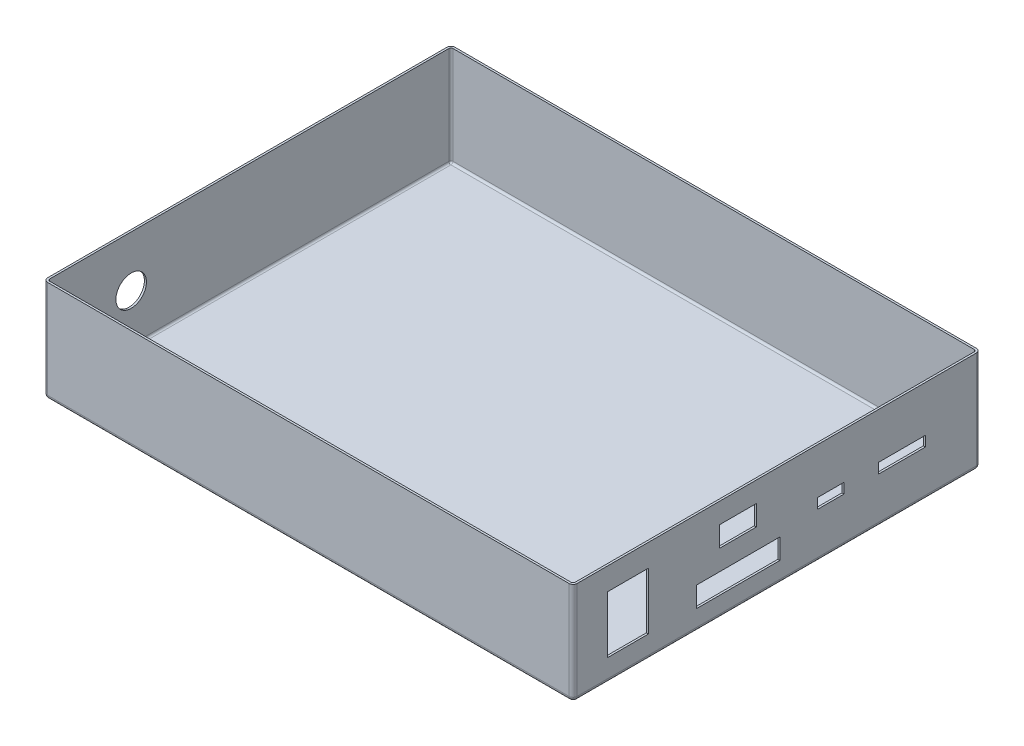
SolidWorks part; units mm, degrees
ref_plane "Front Plane" through (0, 0, 0) normal (0, 0, 1) x (1, 0, 0)
ref_plane "Top Plane" through (0, 0, 0) normal (0, 1, 0) x (1, 0, 0)
ref_plane "Right Plane" through (0, 0, 0) normal (1, 0, 0) x (0, 0, -1)
sketch "Sketch1" plane through (0, 0, 0) normal (0, 1, 0) x (1, 0, 0)
  line L1 (130, -100) -> (-130, -100)
  line L2 (130, -100) -> (130, 100)
  line L3 (130, 100) -> (-130, 100)
  line L4 (-130, -100) -> (-130, 100)
  line L5 (130, -100) -> (-130, 100) construction
  line L6 (130, 100) -> (-130, -100) construction
  point P0 (0, 0)
  dimension "D1" = 260
  dimension "D2" = 200
extrude "Boss-Extrude1" add sketch "Sketch1" along normal blind 50
fillet "Fillet1" radius 2 8 edges at (0, 0, 100) (-130, 25, 100) (-130, 0, 0) (-130, 25, -100) (0, 0, -100) (130, 0, 0) (130, 25, -100) (130, 25, 100)
shell "Shell1" thickness 1
sketch "Sketch2" plane through (130, 0, 0) normal (1, 0, 0) x (0, 0, -1)
  line L0 (-144.0315, 25) -> (119.5021, 25) construction
  line L1 (-98, 50) -> (98, 50) construction
  line L2 (-100, 0) -> (100, 0) construction
  line L3 (98, 2) -> (98, 50) construction
  line L4 (-39.5, 10) -> (1.5, 10)
  line L5 (-39.5, 10) -> (-39.5, 20)
  line L6 (-39.5, 20) -> (1.5, 20)
  line L7 (1.5, 10) -> (1.5, 20)
  line L8 (-39.5, 10) -> (1.5, 20) construction
  line L9 (-39.5, 20) -> (1.5, 10) construction
  line L10 (-28, 30) -> (-10, 30)
  line L11 (-28, 30) -> (-28, 40)
  line L12 (-28, 40) -> (-10, 40)
  line L13 (-10, 30) -> (-10, 40)
  line L14 (-28, 30) -> (-10, 40) construction
  line L15 (-28, 40) -> (-10, 30) construction
  line L17 (-98, 50) -> (-98, 2) construction
  line L18 (20, 22.5) -> (33, 22.5)
  line L19 (20, 22.5) -> (20, 27.5)
  line L20 (20, 27.5) -> (33, 27.5)
  line L21 (33, 22.5) -> (33, 27.5)
  line L22 (20, 22.5) -> (33, 27.5) construction
  line L23 (20, 27.5) -> (33, 22.5) construction
  line L24 (50, 22.5) -> (73, 22.5)
  line L25 (50, 22.5) -> (50, 27.5)
  line L26 (50, 27.5) -> (73, 27.5)
  line L27 (73, 22.5) -> (73, 27.5)
  line L28 (50, 22.5) -> (73, 27.5) construction
  line L29 (50, 27.5) -> (73, 22.5) construction
  line L30 (-83, 11) -> (-63, 11)
  line L31 (-83, 11) -> (-83, 39)
  line L32 (-83, 39) -> (-63, 39)
  line L33 (-63, 11) -> (-63, 39)
  line L34 (-83, 11) -> (-63, 39) construction
  line L35 (-83, 39) -> (-63, 11) construction
  point P6 (-19, 15)
  point P11 (-19, 35)
  point P18 (-73, 25)
  point P19 (26.5, 25)
  point P24 (61.5, 25)
  dimension "D1" = 41
  dimension "D2" = 10
  dimension "D3" = 18
  dimension "D4" = 25
  dimension "D5" = 10
  dimension "D6" = 13
  dimension "D7" = 5
  dimension "D8" = 30
  dimension "D9" = 23
  dimension "D10" = 5
  dimension "D11" = 17
  dimension "D12" = 10
  dimension "D13" = 28
  dimension "D14" = 20
  dimension "D15" = 15
extrude "Cut-Extrude1" cut sketch "Sketch2" against normal blind 50
sketch "Sketch3" plane through (-130, 0, 0) normal (-1, 0, 0) x (0, 0, 1)
  line L2 (-117.1186, 25) -> (135.192, 25) construction
  line L3 (98, 2) -> (98, 50) construction
  circle A0 centre (58, 25) radius 7.5
  dimension "D1" = 15
  dimension "D2" = 25
  dimension "D3" = 40
extrude "Cut-Extrude2" cut sketch "Sketch3" against normal blind 50
